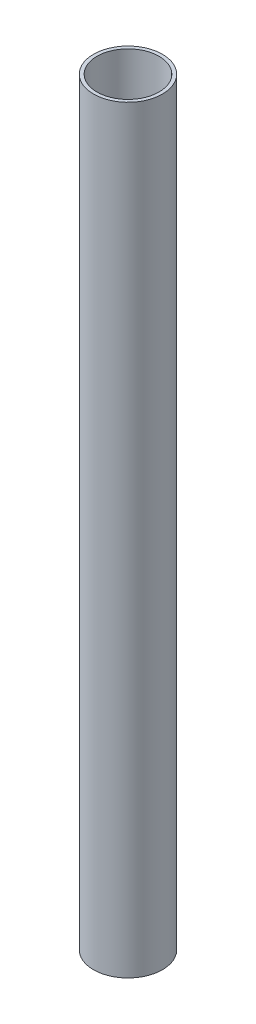
SolidWorks part; units mm, degrees
ref_plane "前视基准面" through (0, 0, 0) normal (0, 0, 1) x (1, 0, 0)
ref_plane "上视基准面" through (0, 0, 0) normal (0, 1, 0) x (1, 0, 0)
ref_plane "右视基准面" through (0, 0, 0) normal (1, 0, 0) x (0, 0, -1)
sketch "草图1" plane through (0, 0, 0) normal (0, 1, 0) x (1, 0, 0)
  circle A0 centre (0, 0) radius 10
  dimension "D1" = 20
extrude "1mm" add sketch "草图1" along normal mid plane 220 thin thin type one direction reverse wall 1
